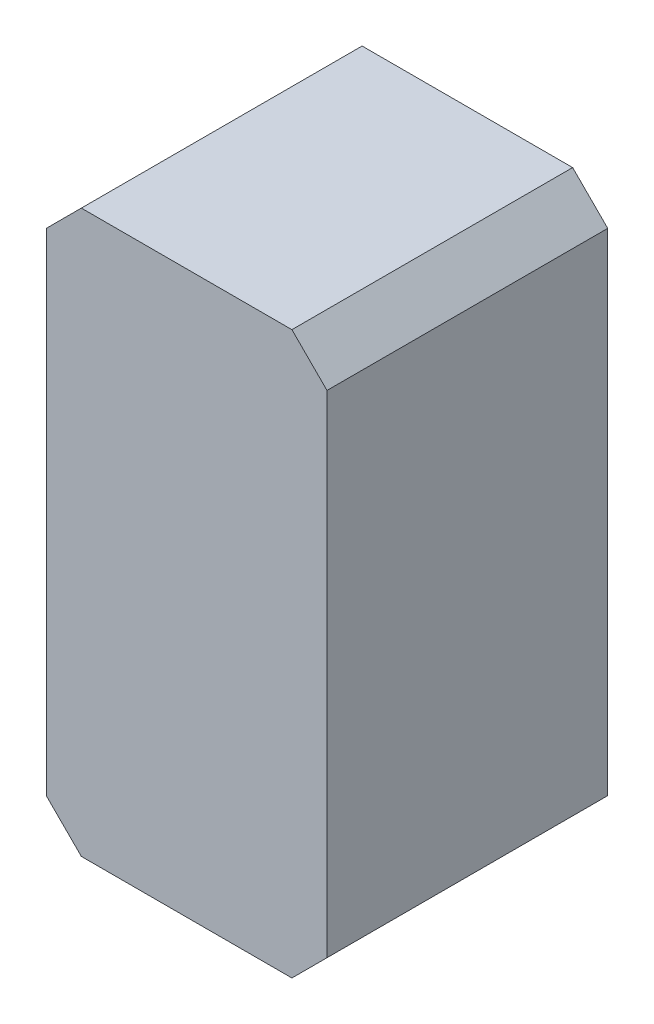
SolidWorks part; units mm, degrees
ref_plane "Front Plane" through (0, 0, 0) normal (0, 0, 1) x (1, 0, 0)
ref_plane "Top Plane" through (0, 0, 0) normal (0, 1, 0) x (1, 0, 0)
ref_plane "Right Plane" through (0, 0, 0) normal (1, 0, 0) x (0, 0, -1)
sketch "Sketch1" plane through (0, 0, 0) normal (0, 0, 1) x (1, 0, 0)
  line L0 (0, 4) -> (0, -4) construction
  line L1 (-2, 4) -> (2, 4)
  line L2 (-2, 4) -> (-2, -4)
  line L3 (-2, -4) -> (2, -4)
  line L4 (2, 4) -> (2, -4)
  line L5 (2, 0) -> (-2, 0) construction
  point P0 (0, 4)
  point P9 (-2, 0)
  dimension "D1" = 4
  dimension "D2" = 8
extrude "Boss-Extrude1" add sketch "Sketch1" along normal blind 4
chamfer "Chamfer1" distance 0.5 distance2 0.5 4 edges at (-2, -4, 2) (2, -4, 2) (-2, 4, 2) (2, 4, 2)
